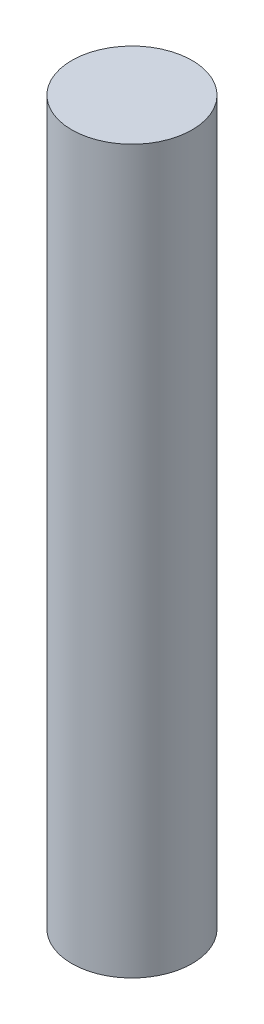
SolidWorks part; units mm, degrees
ref_plane "Front Plane" through (0, 0, 0) normal (0, 0, 1) x (1, 0, 0)
ref_plane "Top Plane" through (0, 0, 0) normal (0, 1, 0) x (1, 0, 0)
ref_plane "Right Plane" through (0, 0, 0) normal (1, 0, 0) x (0, 0, -1)
sketch "Sketch1" plane through (0, 0, 0) normal (0, 1, 0) x (1, 0, 0)
  circle A1 centre (0, 0) radius 0.1875
  dimension "D1" = 0.375
extrude "Boss-Extrude1" add sketch "Sketch1" along normal blind 2.25
